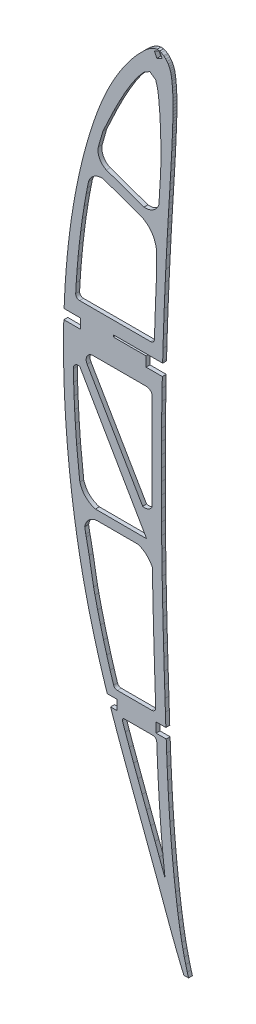
SolidWorks part; units mm, degrees
ref_plane "前视基准面" through (0, 0, 0) normal (0, 0, 1) x (1, 0, 0)
ref_plane "上视基准面" through (0, 0, 0) normal (0, 1, 0) x (1, 0, 0)
ref_plane "右视基准面" through (0, 0, 0) normal (1, 0, 0) x (0, 0, -1)
sketch "Model" plane through (0, 0, 0) normal (0, 0, 1) x (1, 0, 0)
  line L0 (88.2844, 4.0982) -> (87.3563, 6.2458)
  line L1 (87.3563, 6.2458) -> (86.1338, 9.1862)
  line L2 (86.1338, 9.1862) -> (84.936, 12.1378)
  line L3 (84.936, 12.1378) -> (83.7846, 15.0543)
  line L4 (83.7846, 15.0543) -> (82.659, 17.979)
  line L5 (82.659, 17.979) -> (81.552, 20.9115)
  line L6 (81.552, 20.9115) -> (80.4599, 23.8487)
  line L7 (80.4599, 23.8487) -> (79.3775, 26.7913)
  line L8 (79.3775, 26.7913) -> (78.3001, 29.7351)
  line L9 (78.3001, 29.7351) -> (77.2225, 32.6809)
  line L10 (77.2225, 32.6809) -> (75.0559, 38.564)
  line L11 (75.0559, 38.564) -> (72.8745, 44.4394)
  line L12 (72.8745, 44.4394) -> (70.6814, 50.3083)
  line L13 (70.6814, 50.3083) -> (68.4795, 56.1739)
  line L14 (68.4795, 56.1739) -> (66.2726, 62.0382)
  line L15 (66.2726, 62.0382) -> (64.0627, 67.9024)
  line L16 (64.0627, 67.9024) -> (61.8537, 73.7696)
  line L17 (61.8537, 73.7696) -> (59.6618, 79.6096)
  line L18 (59.6618, 79.6096) -> (57.4869, 85.4533)
  line L19 (57.4869, 85.4533) -> (55.3385, 91.3061)
  line L20 (55.3385, 91.3061) -> (53.2297, 97.1717)
  line L21 (53.2297, 97.1717) -> (50.6716, 104.525)
  line L22 (48.987, 109.525) -> (47.244, 114.8915)
  line L23 (47.244, 114.8915) -> (45.4381, 120.7203)
  line L24 (45.4381, 120.7203) -> (43.7142, 126.5726)
  line L25 (43.7142, 126.5726) -> (42.0732, 132.4497)
  line L26 (42.0732, 132.4497) -> (40.5175, 138.3484)
  line L27 (40.5175, 138.3484) -> (39.0468, 144.2689)
  line L28 (39.0468, 144.2689) -> (37.6632, 150.2122)
  line L29 (37.6632, 150.2122) -> (36.3679, 156.1764)
  line L30 (36.3679, 156.1764) -> (35.181, 162.0612)
  line L31 (35.181, 162.0612) -> (34.0797, 167.9598)
  line L32 (34.0797, 167.9598) -> (33.0598, 173.8729)
  line L33 (33.0598, 173.8729) -> (32.1194, 179.7985)
  line L34 (32.1194, 179.7985) -> (31.2566, 185.7366)
  line L35 (31.2566, 185.7366) -> (30.4683, 191.6868)
  line L36 (30.4683, 191.6868) -> (29.7526, 197.6473)
  line L37 (29.7526, 197.6473) -> (29.1103, 203.5789)
  line L38 (29.1103, 203.5789) -> (28.5388, 209.5156)
  line L39 (28.5388, 209.5156) -> (28.0371, 215.4584)
  line L40 (28.0371, 215.4584) -> (27.6063, 221.4053)
  line L41 (27.6063, 221.4053) -> (27.2483, 227.3573)
  line L42 (27.2483, 227.3573) -> (26.9622, 233.3145)
  line L43 (26.9622, 233.3145) -> (26.751, 239.276)
  line L44 (26.751, 239.276) -> (26.6123, 245.2486)
  line L45 (26.6123, 245.2486) -> (26.5507, 251.2206)
  line L46 (26.5507, 251.2206) -> (26.5653, 257.1919)
  line L47 (26.5653, 257.1919) -> (26.66, 263.1617)
  line L48 (26.66, 263.1617) -> (26.6999, 264.525)
  line L49 (26.8517, 269.525) -> (27.0917, 275.0989)
  line L50 (27.0917, 275.0989) -> (27.4328, 281.0655)
  line L51 (27.4328, 281.0655) -> (27.865, 287.0981)
  line L52 (27.865, 287.0981) -> (28.3888, 293.1217)
  line L53 (28.3888, 293.1217) -> (29.0071, 299.1344)
  line L54 (29.0071, 299.1344) -> (29.726, 305.1354)
  line L55 (29.726, 305.1354) -> (30.5496, 311.1231)
  line L56 (30.5496, 311.1231) -> (31.4811, 317.0944)
  line L57 (31.4811, 317.0944) -> (32.5254, 323.0476)
  line L58 (32.5254, 323.0476) -> (33.1036, 326.0807)
  line L59 (33.1036, 326.0807) -> (33.7122, 329.1071)
  line L60 (33.7122, 329.1071) -> (34.3521, 332.1269)
  line L61 (34.3521, 332.1269) -> (35.0243, 335.1391)
  line L62 (35.0243, 335.1391) -> (35.7269, 338.1446)
  line L63 (35.7269, 338.1446) -> (36.4638, 341.1426)
  line L64 (36.4638, 341.1426) -> (37.2321, 344.133)
  line L65 (37.2321, 344.133) -> (38.0574, 347.1949)
  line L66 (38.0574, 347.1949) -> (38.9181, 350.2463)
  line L67 (38.9181, 350.2463) -> (39.8194, 353.2855)
  line L68 (39.8194, 353.2855) -> (40.7623, 356.3115)
  line L69 (40.7623, 356.3115) -> (41.7498, 359.3235)
  line L70 (41.7498, 359.3235) -> (42.7851, 362.3205)
  line L71 (42.7851, 362.3205) -> (43.87, 365.3027)
  line L72 (43.87, 365.3027) -> (44.4524, 366.8425)
  line L73 (44.4524, 366.8425) -> (45.0501, 368.3771)
  line L74 (45.0501, 368.3771) -> (45.663, 369.9042)
  line L75 (45.663, 369.9042) -> (46.2913, 371.4251)
  line L76 (46.2913, 371.4251) -> (46.9369, 372.9377)
  line L77 (46.9369, 372.9377) -> (47.601, 374.4411)
  line L78 (47.601, 374.4411) -> (48.2825, 375.9352)
  line L79 (48.2825, 375.9352) -> (49.0183, 377.4918)
  line L80 (49.0183, 377.4918) -> (49.7755, 379.0383)
  line L81 (49.7755, 379.0383) -> (50.5543, 380.5728)
  line L82 (50.5543, 380.5728) -> (51.3576, 382.0982)
  line L83 (51.3576, 382.0982) -> (52.1852, 383.6138)
  line L84 (52.1852, 383.6138) -> (53.0373, 385.1214)
  line L85 (53.0373, 385.1214) -> (53.9157, 386.6211)
  line L86 (53.9157, 386.6211) -> (54.8944, 388.2324)
  line L87 (54.8944, 388.2324) -> (55.9027, 389.8279)
  line L88 (55.9027, 389.8279) -> (56.937, 391.4035)
  line L89 (56.937, 391.4035) -> (57.9954, 392.9521)
  line L90 (57.9954, 392.9521) -> (59.0773, 394.4697)
  line L91 (59.0773, 394.4697) -> (60.1798, 395.9482)
  line L92 (60.1798, 395.9482) -> (61.3003, 397.3835)
  line L93 (61.3003, 397.3835) -> (61.9985, 398.2428)
  line L94 (61.9985, 398.2428) -> (62.7082, 399.0895)
  line L95 (62.7082, 399.0895) -> (63.4363, 399.9291)
  line L96 (63.4363, 399.9291) -> (64.1893, 400.7707)
  line L97 (64.1893, 400.7707) -> (64.9711, 401.6176)
  line L98 (64.9711, 401.6176) -> (65.7903, 402.4792)
  line L99 (65.7903, 402.4792) -> (66.6517, 403.3586)
  line L100 (66.6517, 403.3586) -> (67.8533, 404.5411)
  line L101 (67.8533, 404.5411) -> (69.1212, 405.6955)
  line L102 (69.1212, 405.6955) -> (70.4386, 406.747)
  line L103 (70.4386, 406.747) -> (71.7896, 407.6228)
  line L104 (71.7896, 407.6228) -> (73.1566, 408.249)
  line L105 (73.1566, 408.249) -> (74.5247, 408.553)
  line L106 (74.5247, 408.553) -> (75.875, 408.4598)
  line L107 (75.875, 408.4598) -> (76.7022, 408.1746)
  line L108 (76.7022, 408.1746) -> (77.9079, 407.4242)
  line L109 (77.9079, 407.4242) -> (78.2684, 407.1509)
  line L110 (78.2684, 407.1509) -> (78.9822, 406.4604)
  line L111 (78.9822, 406.4604) -> (79.6356, 405.6852)
  line L112 (79.6356, 405.6852) -> (80.2137, 404.8476)
  line L113 (80.2137, 404.8476) -> (80.7064, 403.9722)
  line L114 (80.7064, 403.9722) -> (81.0652, 403.1821)
  line L115 (81.0652, 403.1821) -> (81.3553, 402.383)
  line L116 (81.3553, 402.383) -> (81.5877, 401.5754)
  line L117 (81.5877, 401.5754) -> (81.7724, 400.7617)
  line L118 (81.7724, 400.7617) -> (81.9183, 399.9433)
  line L119 (81.9183, 399.9433) -> (82.0363, 399.1196)
  line L120 (82.0363, 399.1196) -> (82.1364, 398.2932)
  line L121 (82.1364, 398.2932) -> (82.29, 396.8155)
  line L122 (82.29, 396.8155) -> (82.4178, 395.3337)
  line L123 (82.4178, 395.3337) -> (82.5208, 393.8467)
  line L124 (82.5208, 393.8467) -> (82.6008, 392.3568)
  line L125 (82.6008, 392.3568) -> (82.659, 390.8649)
  line L126 (82.659, 390.8649) -> (82.6971, 389.3722)
  line L127 (82.6971, 389.3722) -> (82.7173, 387.8786)
  line L128 (82.7173, 387.8786) -> (82.7195, 386.3833)
  line L129 (82.7195, 386.3833) -> (82.7066, 384.8893)
  line L130 (82.7066, 384.8893) -> (82.6807, 383.3968)
  line L131 (82.6807, 383.3968) -> (82.6448, 381.9048)
  line L132 (82.6448, 381.9048) -> (82.5998, 380.4124)
  line L133 (82.5998, 380.4124) -> (82.5488, 378.9208)
  line L134 (82.5488, 378.9208) -> (82.4939, 377.4289)
  line L135 (82.4939, 377.4289) -> (82.436, 375.934)
  line L136 (82.436, 375.934) -> (82.3771, 374.44)
  line L137 (82.3771, 374.44) -> (82.3152, 372.9459)
  line L138 (82.3152, 372.9459) -> (82.2514, 371.4517)
  line L139 (82.2514, 371.4517) -> (82.1854, 369.9584)
  line L140 (82.1854, 369.9584) -> (82.1166, 368.464)
  line L141 (82.1166, 368.464) -> (82.0447, 366.9694)
  line L142 (82.0447, 366.9694) -> (81.8931, 363.9769)
  line L143 (81.8931, 363.9769) -> (81.7304, 360.986)
  line L144 (81.7304, 360.986) -> (81.5606, 357.9957)
  line L145 (81.5606, 357.9957) -> (81.3839, 355.0062)
  line L146 (81.3839, 355.0062) -> (81.2041, 352.0175)
  line L147 (81.2041, 352.0175) -> (81.0213, 349.0277)
  line L148 (81.0213, 349.0277) -> (80.8386, 346.0369)
  line L149 (80.8386, 346.0369) -> (80.6569, 343.0461)
  line L150 (80.6569, 343.0461) -> (80.4771, 340.0564)
  line L151 (80.4771, 340.0564) -> (80.2994, 337.0658)
  line L152 (80.2994, 337.0658) -> (80.1246, 334.0763)
  line L153 (80.1246, 334.0763) -> (79.9529, 331.086)
  line L154 (79.9529, 331.086) -> (79.7842, 328.0958)
  line L155 (79.7842, 328.0958) -> (79.6195, 325.1038)
  line L156 (79.6195, 325.1038) -> (79.3029, 319.1273)
  line L157 (79.3029, 319.1273) -> (79.0013, 313.1514)
  line L158 (79.0013, 313.1514) -> (78.7176, 307.1764)
  line L159 (78.7176, 307.1764) -> (78.4511, 301.2)
  line L160 (78.4511, 301.2) -> (78.2025, 295.2235)
  line L161 (78.2025, 295.2235) -> (77.9731, 289.2438)
  line L162 (77.9731, 289.2438) -> (77.7618, 283.2629)
  line L163 (77.7618, 283.2629) -> (77.5711, 277.2909)
  line L164 (77.5711, 277.2909) -> (77.3994, 271.3207)
  line L165 (77.3994, 271.3207) -> (77.3792, 270.525)
  line L166 (77.2293, 264.525) -> (77.115, 259.38)
  line L167 (77.115, 259.38) -> (77.0013, 253.4093)
  line L168 (77.0013, 253.4093) -> (76.9077, 247.4366)
  line L169 (76.9077, 247.4366) -> (76.8332, 241.4626)
  line L170 (76.8332, 241.4626) -> (76.7785, 235.4956)
  line L171 (76.7785, 235.4956) -> (76.7417, 229.5293)
  line L172 (76.7417, 229.5293) -> (76.7228, 223.5648)
  line L173 (76.7228, 223.5648) -> (76.722, 217.6001)
  line L174 (76.722, 217.6001) -> (76.7372, 211.635)
  line L175 (76.7372, 211.635) -> (76.7674, 205.6697)
  line L176 (76.7674, 205.6697) -> (76.8138, 199.702)
  line L177 (76.8138, 199.702) -> (76.875, 193.738)
  line L178 (76.875, 193.738) -> (76.9491, 187.7766)
  line L179 (76.9491, 187.7766) -> (77.0382, 181.8158)
  line L180 (77.0382, 181.8158) -> (77.1402, 175.8566)
  line L181 (77.1402, 175.8566) -> (77.2563, 169.896)
  line L182 (77.2563, 169.896) -> (77.3854, 163.9359)
  line L183 (77.3854, 163.9359) -> (77.5277, 157.9734)
  line L184 (77.5277, 157.9734) -> (77.6818, 152.0135)
  line L185 (77.6818, 152.0135) -> (77.8478, 146.0551)
  line L186 (77.8478, 146.0551) -> (78.0238, 140.0991)
  line L187 (78.0238, 140.0991) -> (78.2078, 134.1424)
  line L188 (78.2078, 134.1424) -> (78.3998, 128.1861)
  line L189 (78.3998, 128.1861) -> (78.5978, 122.2291)
  line L190 (78.5978, 122.2291) -> (78.8, 116.2693)
  line L191 (78.8, 116.2693) -> (79.0357, 109.525)
  line L192 (79.2179, 104.525) -> (79.4571, 98.3979)
  line L193 (79.4571, 98.3979) -> (79.7131, 92.4444)
  line L194 (79.7131, 92.4444) -> (79.9979, 86.4932)
  line L195 (79.9979, 86.4932) -> (80.3198, 80.5415)
  line L196 (80.3198, 80.5415) -> (80.6847, 74.5918)
  line L197 (80.6847, 74.5918) -> (81.0989, 68.6362)
  line L198 (81.0989, 68.6362) -> (81.5659, 62.6859)
  line L199 (81.5659, 62.6859) -> (82.0887, 56.741)
  line L200 (82.0887, 56.741) -> (82.6714, 50.8008)
  line L201 (82.6714, 50.8008) -> (83.3168, 44.8663)
  line L202 (83.3168, 44.8663) -> (84.0301, 38.9368)
  line L203 (84.0301, 38.9368) -> (84.8123, 33.0123)
  line L204 (84.8123, 33.0123) -> (85.2347, 30.0319)
  line L205 (85.2347, 30.0319) -> (85.682, 27.0555)
  line L206 (85.682, 27.0555) -> (86.16, 24.0846)
  line L207 (86.16, 24.0846) -> (86.6737, 21.1221)
  line L208 (86.6737, 21.1221) -> (87.2301, 18.1676)
  line L209 (87.2301, 18.1676) -> (87.8361, 15.2242)
  line L210 (87.8361, 15.2242) -> (88.4956, 12.2932)
  line L211 (88.4956, 12.2932) -> (89.228, 9.3183)
  line L212 (89.228, 9.3183) -> (90.014, 6.3568)
  line L213 (90.014, 6.3568) -> (90.683, 4.0982)
  line L214 (90.683, 4.0982) -> (88.2844, 4.0982)
  line L215 (76.3839, 355.0062) -> (76.2041, 352.0175)
  line L216 (76.2041, 352.0175) -> (76.0213, 349.0277)
  line L217 (76.0213, 349.0277) -> (75.8386, 346.0369)
  line L218 (75.8386, 346.0369) -> (75.6569, 343.0461)
  line L219 (75.6569, 343.0461) -> (75.4771, 340.0564)
  line L220 (74.1811, 316.6885) -> (74.3575, 310.1962)
  line L221 (74.3575, 310.1962) -> (74.091, 304.2198)
  line L222 (74.091, 304.2198) -> (73.8424, 298.2433)
  line L223 (73.8424, 298.2433) -> (73.613, 292.2636)
  line L224 (73.613, 292.2636) -> (73.4017, 286.2827)
  line L225 (73.4017, 286.2827) -> (73.211, 280.3107)
  line L226 (73.211, 280.3107) -> (73.173, 278.9873)
  line L227 (71.1738, 277.0448) -> (34.7878, 277.0448)
  line L228 (32.7911, 279.159) -> (33.0727, 284.0853)
  line L229 (33.0727, 284.0853) -> (33.5049, 290.1179)
  line L230 (33.5049, 290.1179) -> (34.0287, 296.1415)
  line L231 (34.0287, 296.1415) -> (34.647, 302.1542)
  line L232 (34.647, 302.1542) -> (35.3659, 308.1552)
  line L233 (35.3659, 308.1552) -> (36.1895, 314.1428)
  line L234 (36.1895, 314.1428) -> (37.121, 320.1142)
  line L235 (37.121, 320.1142) -> (38.1653, 326.0674)
  line L236 (38.1653, 326.0674) -> (38.7435, 329.1005)
  line L237 (38.7435, 329.1005) -> (39.3521, 332.1269)
  line L238 (57.6926, 102.7305) -> (72.3643, 102.7305)
  line L239 (74.3628, 100.8087) -> (74.4571, 98.3979)
  line L240 (74.4571, 98.3979) -> (74.7131, 92.4444)
  line L241 (74.7131, 92.4444) -> (74.9979, 86.4932)
  line L242 (74.9979, 86.4932) -> (75.3198, 80.5415)
  line L243 (75.3198, 80.5415) -> (75.6847, 74.5918)
  line L244 (75.6847, 74.5918) -> (76.0989, 68.6362)
  line L245 (76.0989, 68.6362) -> (76.5659, 62.6859)
  line L246 (76.5659, 62.6859) -> (77.0887, 56.741)
  line L247 (77.0887, 56.741) -> (77.6714, 50.8008)
  line L248 (77.6714, 50.8008) -> (78.6048, 42.4723)
  line L249 (78.6048, 42.4723) -> (77.8745, 44.4394)
  line L250 (77.8745, 44.4394) -> (75.6814, 50.3083)
  line L251 (75.6814, 50.3083) -> (73.4795, 56.1739)
  line L252 (73.4795, 56.1739) -> (71.2726, 62.0382)
  line L253 (71.2726, 62.0382) -> (69.0627, 67.9024)
  line L254 (69.0627, 67.9024) -> (66.8537, 73.7696)
  line L255 (66.8537, 73.7696) -> (64.6618, 79.6096)
  line L256 (64.6618, 79.6096) -> (62.4869, 85.4533)
  line L257 (62.4869, 85.4533) -> (60.3385, 91.3061)
  line L258 (60.3385, 91.3061) -> (58.2297, 97.1717)
  line L259 (58.2297, 97.1717) -> (57.2148, 100.0695)
  line L260 (72.1983, 172.8763) -> (72.2563, 169.896)
  line L261 (72.2563, 169.896) -> (72.3854, 163.9359)
  line L262 (72.3854, 163.9359) -> (72.5277, 157.9734)
  line L263 (72.5277, 157.9734) -> (72.6818, 152.0135)
  line L264 (72.6818, 152.0135) -> (72.8478, 146.0551)
  line L265 (72.8478, 146.0551) -> (72.9828, 141.4867)
  line L266 (26.8517, 269.525) -> (34.1731, 269.525)
  line L267 (48.4843, 341.9392) -> (67.8591, 335.1093)
  line L268 (46.9662, 337.1629) -> (66.7011, 330.1505)
  line L269 (68.8902, 269.525) -> (52.1038, 269.525)
  line L270 (52.1038, 269.525) -> (52.1038, 270.525)
  line L271 (52.1038, 270.525) -> (77.3792, 270.525)
  line L272 (48.987, 109.525) -> (53.987, 109.525)
  line L273 (53.987, 109.525) -> (53.987, 104.525)
  line L274 (53.987, 104.525) -> (50.6716, 104.525)
  line L275 (79.0357, 109.525) -> (74.0357, 109.525)
  line L276 (74.0357, 109.525) -> (74.0357, 104.525)
  line L277 (74.0357, 104.525) -> (79.2179, 104.525)
  line L278 (75.8662, 408.407) -> (73.1403, 407.1539)
  line L279 (73.1403, 407.1539) -> (74.3933, 404.429)
  line L280 (74.3933, 404.429) -> (77.1183, 405.681)
  line L281 (77.1183, 405.681) -> (75.8662, 408.407)
  line L282 (35.1731, 264.525) -> (35.1731, 269.525)
  line L283 (35.1731, 269.525) -> (34.1731, 269.525)
  line L284 (68.8902, 264.525) -> (68.8902, 269.525)
  line L285 (57.2148, 100.0695) -> (56.7488, 101.4)
  line L287 (72.1277, 177.1516) -> (72.1983, 172.8763)
  line L288 (37.424, 177.9507) -> (37.9332, 174.9324)
  line L289 (43.6206, 183.7826) -> (64.7396, 183.7826)
  line L290 (38.2051, 173.7578) -> (39.6982, 166.2423)
  line L291 (37.9332, 174.9324) -> (38.2051, 173.7578)
  line L292 (73.4035, 127.9565) -> (73.8, 116.2693)
  line L293 (73.8, 116.2693) -> (73.8217, 115.6447)
  line L294 (71.8229, 113.5752) -> (54.126, 113.5752)
  line L295 (52.2156, 114.9833) -> (50.4381, 120.7203)
  line L296 (50.4381, 120.7203) -> (48.7142, 126.5726)
  line L297 (48.7142, 126.5726) -> (47.0732, 132.4497)
  line L298 (47.0732, 132.4497) -> (45.5175, 138.3484)
  line L299 (45.5175, 138.3484) -> (44.0468, 144.2689)
  line L300 (44.0468, 144.2689) -> (42.6632, 150.2122)
  line L301 (42.6632, 150.2122) -> (41.9726, 153.3919)
  line L302 (33.2662, 212.296) -> (32.6063, 221.4053)
  line L303 (32.6063, 221.4053) -> (32.2483, 227.3573)
  line L304 (32.2483, 227.3573) -> (31.9622, 233.3145)
  line L305 (31.9622, 233.3145) -> (31.751, 239.276)
  line L306 (31.751, 239.276) -> (31.6123, 245.2486)
  line L307 (42.0447, 256.0726) -> (69.05, 256.0726)
  line L308 (72.0048, 253.5917) -> (72.0013, 253.4093)
  line L309 (72.0013, 253.4093) -> (71.9077, 247.4366)
  line L310 (71.9077, 247.4366) -> (71.8592, 243.5463)
  line L311 (35.1731, 264.525) -> (26.6999, 264.525)
  line L312 (68.8902, 264.525) -> (77.2293, 264.525)
  line L313 (46.5711, 357.7155) -> (44.4172, 350.1793)
  line L314 (41.9726, 153.3919) -> (39.6982, 166.2423)
  line L315 (72.9828, 141.4867) -> (73.4035, 127.9565)
  line L316 (71.8592, 243.5463) -> (72.0058, 204.0662)
  line L317 (42.9247, 188.5116) -> (69.1767, 188.4464)
  line L318 (67.1361, 201.8569) -> (38.6369, 250.7185)
  line L319 (69.1767, 188.4464) -> (34.8919, 247.8022)
  line L320 (33.2662, 212.296) -> (34.9082, 196.538)
  line L321 (48.4911, 362.0105) -> (52.1776, 369.8652)
  line L322 (52.1776, 369.8652) -> (55.4148, 376.2066)
  line L323 (55.4148, 376.2066) -> (58.3792, 381.6365)
  line L324 (58.3792, 381.6365) -> (61.6536, 386.9885)
  line L325 (61.6536, 386.9885) -> (64.5611, 391.2325)
  line L326 (64.5611, 391.2325) -> (67.7311, 394.9485)
  line L327 (67.7311, 394.9485) -> (70.8411, 396.7615)
  line L328 (70.8411, 396.7615) -> (73.8613, 394.5719)
  line L329 (73.8613, 394.5719) -> (74.8045, 391.0642)
  line L330 (74.8045, 391.0642) -> (75.2911, 387.9395)
  line L331 (75.2911, 387.9395) -> (76.0511, 379.4035)
  line L332 (76.0511, 379.4035) -> (76.2611, 373.7875)
  line L333 (48.4911, 362.0105) -> (46.7203, 358.2374)
  line L334 (46.7203, 358.2374) -> (46.5711, 357.7155)
  line L335 (76.2611, 373.7875) -> (76.5545, 365.943)
  line L336 (76.5545, 365.943) -> (76.3839, 355.0062)
  arc A0 (57.6926, 102.7305) -> (56.7488, 101.4) centre (57.6926, 101.7305) ccw
  arc A1 (67.8591, 335.1093) -> (75.4771, 340.0564) centre (68.6729, 342.1951) ccw
  arc A2 (44.4172, 350.1793) -> (48.4843, 341.9392) centre (51.4389, 348.5212) ccw
  arc A3 (46.9662, 337.1629) -> (39.3521, 332.1269) centre (46.1852, 330.0697) ccw
  arc A4 (34.9082, 196.538) -> (42.9247, 188.5116) centre (45.7924, 199.3923) ccw
  arc A5 (43.6206, 183.7826) -> (37.424, 177.9507) centre (44.289, 176.8643) ccw
  arc A6 (72.1277, 177.1516) -> (64.7396, 183.7826) centre (60.9374, 172.1149) ccw
  arc A7 (34.8919, 247.8022) -> (31.6123, 245.2486) centre (34.0714, 245.4731) ccw
  arc A8 (42.0447, 256.0726) -> (38.6369, 250.7185) centre (41.7209, 252.5171) ccw
  arc A9 (67.1361, 201.8569) -> (72.0058, 204.0662) centre (68.295, 205.7741) ccw
  arc A10 (74.1811, 316.6885) -> (66.7011, 330.1505) centre (60.7474, 318.0333) ccw
  arc A11 (71.1738, 277.0448) -> (73.173, 278.9873) centre (71.1738, 279.0448) ccw
  arc A12 (32.7911, 279.159) -> (34.7878, 277.0448) centre (34.7878, 279.0448) ccw
  arc A13 (74.3628, 100.8087) -> (72.3643, 102.7305) centre (72.3643, 100.7305) ccw
  arc A14 (71.8229, 113.5752) -> (73.8217, 115.6447) centre (71.8229, 115.5752) ccw
  arc A15 (52.2156, 114.9833) -> (54.126, 113.5752) centre (54.126, 115.5752) ccw
  arc A16 (72.0048, 253.5917) -> (69.05, 256.0726) centre (69.05, 253.0726) ccw
extrude "凸台-拉伸1" add sketch "Model" along normal blind 2
